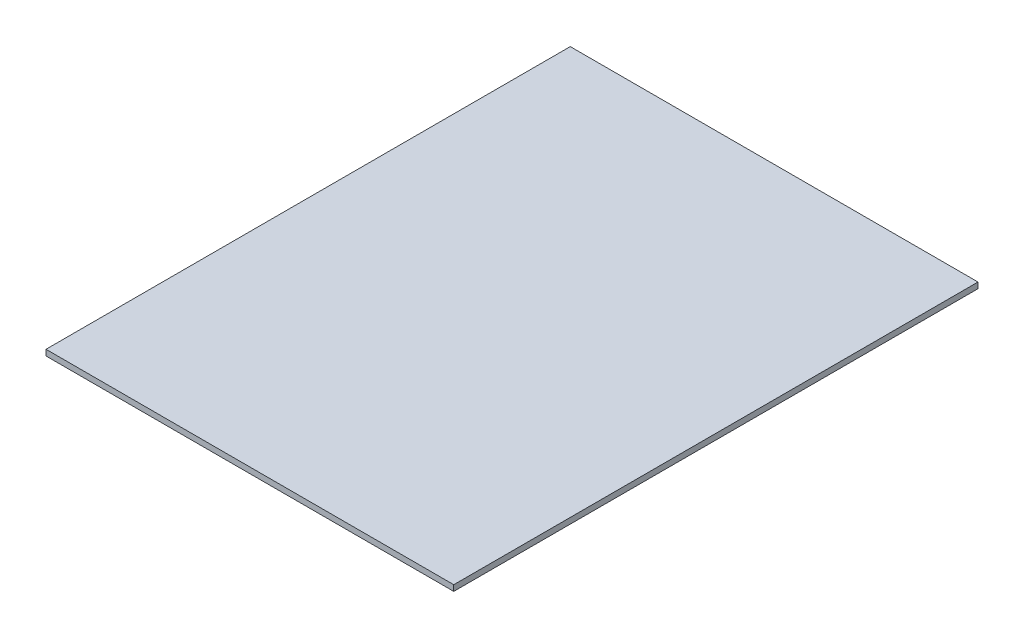
SolidWorks part; units mm, degrees
ref_plane "Front Plane" through (0, 0, 0) normal (0, 0, 1) x (1, 0, 0)
ref_plane "Top Plane" through (0, 0, 0) normal (0, 1, 0) x (1, 0, 0)
ref_plane "Right Plane" through (0, 0, 0) normal (1, 0, 0) x (0, 0, -1)
sketch "Sketch1" plane through (0, 0, 0) normal (0, 1, 0) x (1, 0, 0)
  line L1 (-35, -45) -> (35, -45)
  line L2 (-35, -45) -> (-35, 45)
  line L3 (-35, 45) -> (35, 45)
  line L4 (35, -45) -> (35, 45)
  line L5 (-35, -45) -> (35, 45) construction
  line L6 (-35, 45) -> (35, -45) construction
  point P0 (0, 0)
  dimension "D1" = 70
  dimension "D2" = 90
extrude "Boss-Extrude1" add sketch "Sketch1" along normal blind 1
